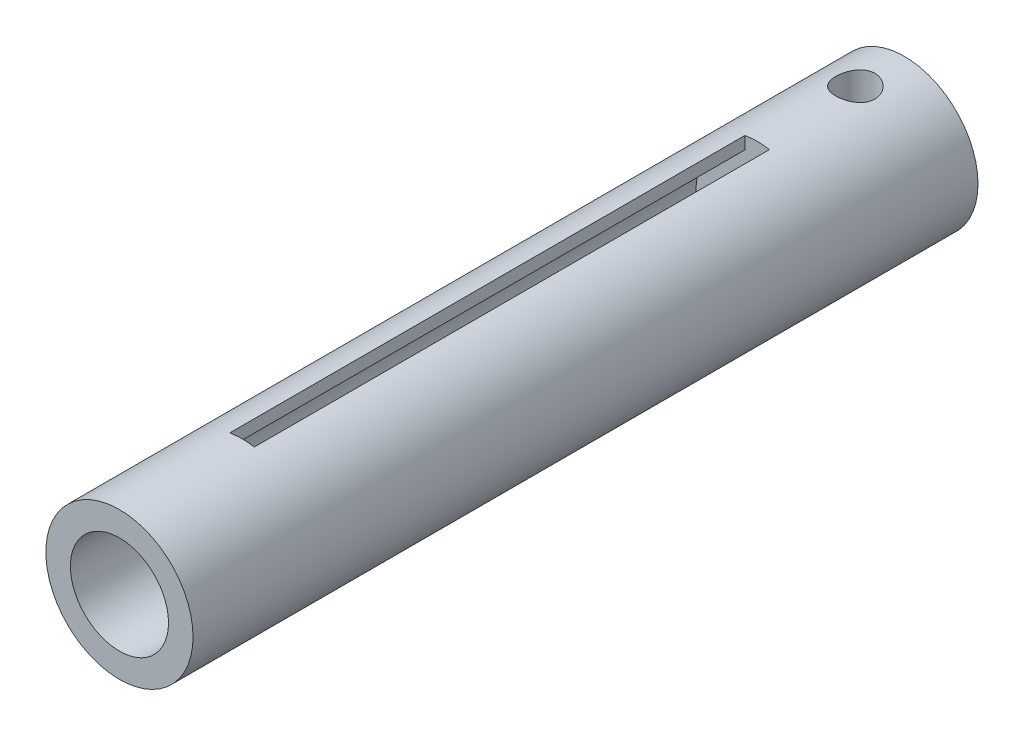
SolidWorks part; units mm, degrees
ref_plane "Front Plane" through (0, 0, 0) normal (0, 0, 1) x (1, 0, 0)
ref_plane "Top Plane" through (0, 0, 0) normal (0, 1, 0) x (1, 0, 0)
ref_plane "Right Plane" through (0, 0, 0) normal (1, 0, 0) x (0, 0, -1)
sketch "Sketch1" plane through (0, 0, 0) normal (0, 0, 1) x (1, 0, 0)
  circle A0 centre (0, 0) radius 15
  dimension "D1" = 30
extrude "Boss-Extrude1" add sketch "Sketch1" along normal blind 150 and the other way blind 10
ref_plane "Plane1" through (0, 0, 125) normal (0, 0, 1) x (1, 0, 0)
sketch "Sketch3" plane through (0, 0, 125) normal (0, 0, 1) x (1, 0, 0)
  circle A0 centre (0, 0) radius 12.5
  dimension "D1" = 25
extrude "Cut-Extrude2" cut sketch "Sketch3" against normal blind 105
sketch "Sketch4" plane through (0, 0, 150) normal (0, 0, 1) x (1, 0, 0)
  circle A0 centre (0, 0) radius 10
  dimension "D1" = 20
extrude "Cut-Extrude3" cut sketch "Sketch4" against normal up to next
sketch "Sketch5" plane through (0, 0, 0) normal (0, 1, 0) x (1, 0, 0)
  line L0 (15, 10) -> (-15, 10) construction
  circle A0 centre (0, 0) radius 4
  dimension "D1" = 8
  dimension "D2" = 10
extrude "Cut-Extrude4" cut sketch "Sketch5" against normal through all and the other way through all
sketch "Sketch6" plane through (0, 0, 0) normal (0, 1, 0) x (1, 0, 0)
  line L0 (-12.5, -20) -> (12.5, -20) construction
  line L1 (-2.5, -20) -> (2.5, -20)
  line L2 (-2.5, -20) -> (-2.5, -125)
  line L3 (-2.5, -125) -> (2.5, -125)
  line L4 (2.5, -20) -> (2.5, -125)
  dimension "D1" = 5
  dimension "D2" = 105
  dimension "D3" = 2.5
  dimension "D4" = 0
extrude "Cut-Extrude12" cut sketch "Sketch6" along normal through all contours L3 L4 L1 L2
